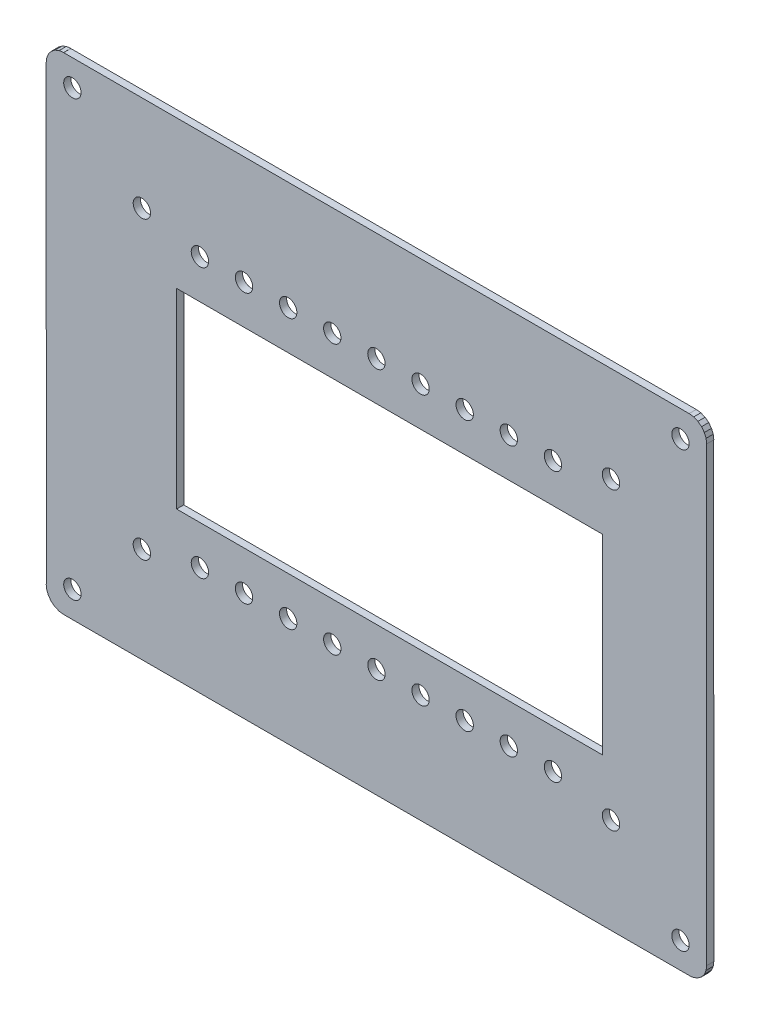
SolidWorks part; units mm, degrees
ref_plane "前视基准面" through (0, 0, 0) normal (0, 0, 1) x (1, 0, 0)
ref_plane "上视基准面" through (0, 0, 0) normal (0, 1, 0) x (1, 0, 0)
ref_plane "右视基准面" through (0, 0, 0) normal (1, 0, 0) x (0, 0, -1)
sketch "草图1" plane through (0, 0, 0) normal (0, 0, 1) x (1, 0, 0)
  line L0 (33.5, 10) -> (9, 10)
  line L1 (9, 10) -> (9, 21)
  line L2 (9, 21) -> (33.5, 21)
  line L3 (33.5, 21) -> (33.5, 10)
  line L4 (1.5257, 2.2389) -> (1.6265, 1.9957)
  line L5 (1.6265, 1.9957) -> (1.7868, 1.7868)
  line L6 (1.7868, 1.7868) -> (1.9957, 1.6265)
  line L7 (1.9957, 1.6265) -> (2.2389, 1.5257)
  line L8 (2.2389, 1.5257) -> (2.5, 1.4914)
  line L9 (2.5, 1.4914) -> (38.5, 1.5)
  line L10 (38.5, 1.5) -> (38.5, 1.4914)
  line L11 (38.5, 1.4914) -> (38.7611, 1.5257)
  line L12 (38.7611, 1.5257) -> (39.0043, 1.6265)
  line L13 (39.0043, 1.6265) -> (39.2132, 1.7868)
  line L14 (39.2132, 1.7868) -> (39.3735, 1.9957)
  line L15 (39.3735, 1.9957) -> (39.4743, 2.2389)
  line L16 (39.4743, 2.2389) -> (39.5086, 2.5)
  line L17 (39.5086, 2.5) -> (39.5, 28.5)
  line L18 (39.5, 28.5) -> (39.5086, 28.5)
  line L19 (39.5086, 28.5) -> (39.4743, 28.7611)
  line L20 (39.4743, 28.7611) -> (39.3735, 29.0043)
  line L21 (39.3735, 29.0043) -> (39.2132, 29.2132)
  line L22 (39.2132, 29.2132) -> (39.0043, 29.3735)
  line L23 (39.0043, 29.3735) -> (38.7611, 29.4743)
  line L24 (38.7611, 29.4743) -> (38.5, 29.5086)
  line L25 (38.5, 29.5086) -> (2.5, 29.5)
  line L26 (2.5, 29.5) -> (2.5, 29.5086)
  line L27 (2.5, 29.5086) -> (2.2389, 29.4743)
  line L28 (2.2389, 29.4743) -> (1.9957, 29.3735)
  line L29 (1.9957, 29.3735) -> (1.7868, 29.2132)
  line L30 (1.7868, 29.2132) -> (1.6265, 29.0043)
  line L31 (1.6265, 29.0043) -> (1.5257, 28.7611)
  line L32 (1.5257, 28.7611) -> (1.4914, 28.5)
  line L33 (1.4914, 28.5) -> (1.5, 2.5)
  line L34 (1.5, 2.5) -> (1.4914, 2.5)
  line L35 (1.4914, 2.5) -> (1.5257, 2.2389)
  circle A0 centre (38, 28) radius 0.5
  circle A1 centre (34, 24) radius 0.5
  circle A2 centre (30.66, 23.25) radius 0.5
  circle A3 centre (28.12, 23.25) radius 0.5
  circle A4 centre (23.04, 23.25) radius 0.5
  circle A5 centre (20.5, 23.25) radius 0.5
  circle A6 centre (25.58, 23.25) radius 0.5
  circle A7 centre (30.66, 7.75) radius 0.5
  circle A8 centre (28.12, 7.75) radius 0.5
  circle A9 centre (38, 3) radius 0.5
  circle A10 centre (34, 7) radius 0.5
  circle A11 centre (23.04, 7.75) radius 0.5
  circle A12 centre (20.5, 7.75) radius 0.5
  circle A13 centre (25.58, 7.75) radius 0.5
  circle A14 centre (15.42, 23.25) radius 0.5
  circle A15 centre (12.88, 23.25) radius 0.5
  circle A16 centre (17.96, 23.25) radius 0.5
  circle A17 centre (7, 24) radius 0.5
  circle A18 centre (3, 28) radius 0.5
  circle A19 centre (10.34, 23.25) radius 0.5
  circle A20 centre (15.42, 7.75) radius 0.5
  circle A21 centre (12.88, 7.75) radius 0.5
  circle A22 centre (17.96, 7.75) radius 0.5
  circle A23 centre (10.34, 7.75) radius 0.5
  circle A24 centre (7, 7) radius 0.5
  circle A25 centre (3, 3) radius 0.5
extrude "凸台-拉伸1" add sketch "草图1" against normal blind 0.4115
sketch "草图2" plane through (0, 0, 0) normal (0, 0, 1) x (1, 0, 0)
  line L0 (110.0995, 239.8236) -> (544.7662, 239.8236) construction
sketch "草图3" plane through (0, 0, -0.4115) normal (0, 0, -1) x (-1, 0, 0)
  line L0 (68.7788, 245.9864) -> (502.7788, 245.9864) construction
